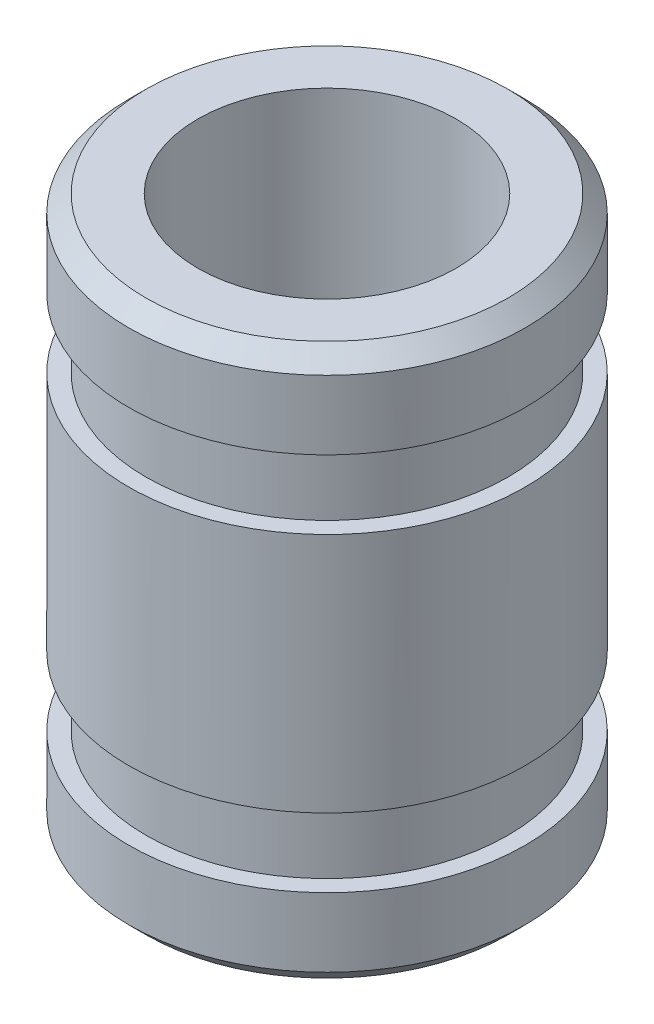
SolidWorks part; units mm, degrees
material "Silicon"
ref_plane "Front" through (0, 0, 0) normal (0, 0, 1) x (1, 0, 0)
ref_plane "Top" through (0, 0, 0) normal (0, 1, 0) x (1, 0, 0)
ref_plane "Right" through (0, 0, 0) normal (1, 0, 0) x (0, 0, -1)
sketch "Sketch1" plane through (0, 0, 0) normal (0, 1, 0) x (1, 0, 0)
  circle A0 centre (0, 0) radius 11.5
  dimension "D1" = 23
extrude "Boss-Extrude1" add sketch "Sketch1" along normal blind 32
sketch "Sketch2" plane through (0, 32, 0) normal (0, 1, 0) x (1, 0, 0)
  circle A0 centre (0, 0) radius 7.5
  dimension "D1" = 15
extrude "Cut-Extrude1" cut sketch "Sketch2" against normal blind 32
sketch "Sketch3" plane through (0, 0, 0) normal (0, 0, 1) x (1, 0, 0)
  line L0 (11.5, 0) -> (11.5, 32) construction
  line L1 (11.5, 9) -> (10.5, 9)
  line L2 (11.5, 9) -> (11.5, 5)
  line L3 (11.5, 5) -> (10.5, 5)
  line L4 (10.5, 9) -> (10.5, 5)
  line L5 (11, 5) -> (11, 9) construction
  line L6 (11.5, 7) -> (10.5, 7) construction
  line L7 (-11.5, 0) -> (11.5, 0) construction
  point P148 (11, 7)
  dimension "D1" = 1
  dimension "D2" = 5
  dimension "D3" = 4
ref_plane "Plane1" through (0, 7, 0) normal (0, -1, 0) x (-1, 0, 0)
sketch "Sketch4" plane through (0, 7, 0) normal (0, -1, 0) x (-1, 0, 0)
  circle A0 centre (0, 0) radius 11
sweep "Cut-Sweep1" cut profiles "Sketch3" path "Sketch4"
ref_plane "Plane2" through (0, 25, 0) normal (0, 1, 0) x (1, 0, 0)
sketch "Sketch5" plane through (0, 0, 0) normal (1, 0, 0) x (0, 0, -1)
  line L0 (11.5, 9) -> (11.5, 32) construction
  line L1 (11.5, 27) -> (10.5, 27)
  line L2 (11.5, 27) -> (11.5, 23)
  line L3 (11.5, 23) -> (10.5, 23)
  line L4 (10.5, 27) -> (10.5, 23)
  line L5 (11, 23) -> (11, 27) construction
  line L6 (11.5, 25) -> (10.5, 25) construction
  line L7 (11.5, 32) -> (-11.5, 32) construction
  point P76 (11, 25)
  dimension "D1" = 5
  dimension "D2" = 4
  dimension "D3" = 1
sketch "Sketch6" plane through (0, 25, 0) normal (0, 1, 0) x (1, 0, 0)
  circle A0 centre (0, 0) radius 11
sweep "Cut-Sweep2" cut profiles "Sketch5" path "Sketch6"
chamfer "Chamfer2" distance 1 angle 45 2 edges at (0, 0, 11.5) (0, 32, 11.5)
